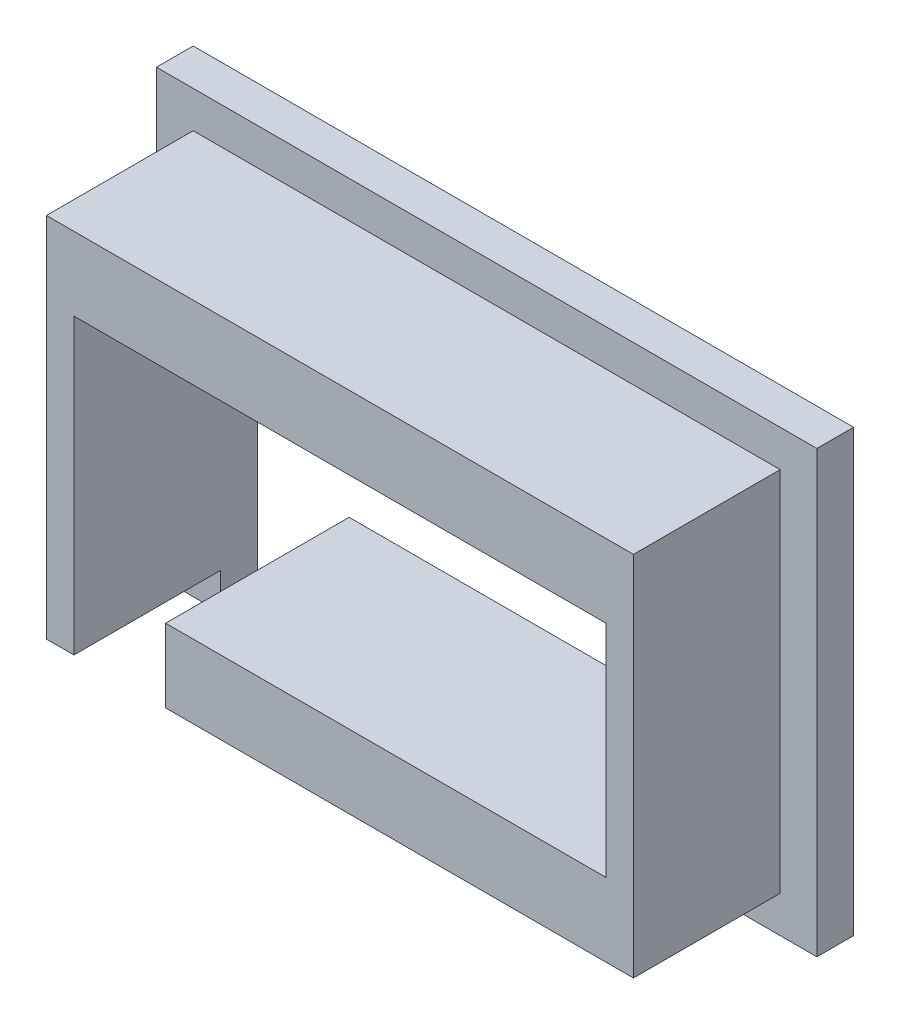
SolidWorks part; units mm, degrees
ref_plane "Front Plane" through (0, 0, 0) normal (0, 0, 1) x (1, 0, 0)
ref_plane "Top Plane" through (0, 0, 0) normal (0, 1, 0) x (1, 0, 0)
ref_plane "Right Plane" through (0, 0, 0) normal (1, 0, 0) x (0, 0, -1)
sketch "Sketch1" plane through (0, 0, 0) normal (0, 0, 1) x (1, 0, 0)
  line L1 (-14.5, 6) -> (14.5, 6)
  line L2 (-14.5, 6) -> (-14.5, -6)
  line L3 (-14.5, -6) -> (14.5, -6)
  line L4 (14.5, 6) -> (14.5, -6)
  line L5 (-14.5, 6) -> (14.5, -6) construction
  line L6 (-14.5, -6) -> (14.5, 6) construction
  line L7 (-16, 10) -> (16, 10)
  line L8 (-16, 10) -> (-16, -10)
  line L9 (-16, -10) -> (16, -10)
  line L10 (16, 10) -> (16, -10)
  line L11 (-16, 10) -> (16, -10) construction
  line L12 (-16, -10) -> (16, 10) construction
  point P0 (0, 0)
  point P6 (0, 0)
  dimension "D1" = 12
  dimension "D2" = 29
  dimension "D3" = 20
  dimension "D4" = 32
extrude "Boss-Extrude1" add sketch "Sketch1" along normal blind 10
sketch "Sketch2" plane through (0, 0, 0) normal (0, 0, -1) x (-1, 0, 0)
  line L0 (18, 12) -> (-18, 12)
  line L1 (16, -10) -> (-16, -10)
  line L2 (16, -10) -> (16, 10)
  line L3 (16, 10) -> (-16, 10)
  line L4 (-16, -10) -> (-16, 10)
  line L5 (16, -10) -> (-16, 10) construction
  line L6 (16, 10) -> (-16, -10) construction
  line L7 (-18, -12) -> (-18, 12)
  line L8 (18, -12) -> (-18, -12)
  line L9 (18, -12) -> (18, 12)
  point P0 (0, 0)
  dimension "D1" = 2
extrude "Boss-Extrude2" add sketch "Sketch2" against normal blind 2 contours L0 L7 L8 L9 | L2 L1 L4 L3
sketch "Sketch3" plane through (0, 0, 0) normal (0, 0, -1) x (-1, 0, 0)
  line L0 (14.5, -6) -> (14.5, -12)
  line L1 (18, -12) -> (-18, -12) construction
  line L2 (14.5, -12) -> (9.5, -12)
  line L3 (9.5, -12) -> (9.5, -6)
  line L4 (14.5, -6) -> (-14.5, -6) construction
  line L5 (9.5, -6) -> (14.5, -6)
  dimension "D1" = 5
extrude "Cut-Extrude2" cut sketch "Sketch3" against normal through all
